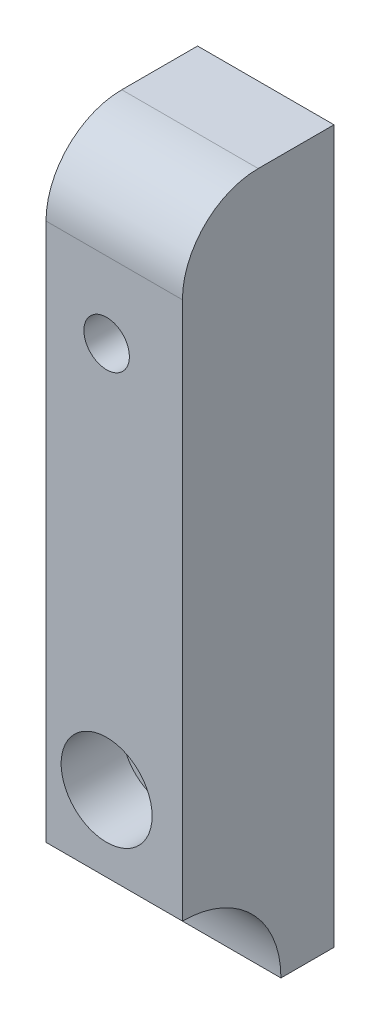
SolidWorks part; units mm, degrees
ref_plane "Front Plane" through (0, 0, 0) normal (0, 0, 1) x (1, 0, 0)
ref_plane "Top Plane" through (0, 0, 0) normal (0, 1, 0) x (1, 0, 0)
ref_plane "Right Plane" through (0, 0, 0) normal (1, 0, 0) x (0, 0, -1)
sketch "Sketch1" plane through (0, 0, 0) normal (0, 0, 1) x (1, 0, 0)
  line L1 (0, 0) -> (10, 0)
  line L2 (0, 0) -> (0, 47)
  line L3 (0, 47) -> (10, 47)
  line L4 (10, 0) -> (10, 47)
  dimension "D1" = 47
  dimension "D2" = 10
extrude "Boss-Extrude1" add sketch "Sketch1" along normal blind 10
sketch "Sketch2" plane through (0, 0, 10) normal (0, 0, 1) x (1, 0, 0)
  circle A0 centre (5, 37) radius 1.5
  circle A1 centre (5, 11.5) radius 1.5
  dimension "D3" = 3
  dimension "D4" = 3
  dimension "D1" = 10
  dimension "D2" = 11.5
extrude "Cut-Extrude1" cut sketch "Sketch2" against normal blind 10
fillet "Fillet1" radius 5 1 edges at (5, 47, 10)
sketch "Sketch3" plane through (0, 0, 0) normal (-1, 0, 0) x (0, 0, 1)
  line L1 (0, 47) -> (10, 47)
  line L2 (0, 47) -> (0, 0)
  line L3 (0, 0) -> (10, 0)
  line L4 (10, 47) -> (10, 0)
extrude "Cut-Extrude2" cut sketch "Sketch3" against normal blind 1
sketch "Sketch4" plane through (1, 0, 0) normal (-1, 0, 0) x (0, 0, 1)
  circle A0 centre (10, 0) radius 6.5
  dimension "D1" = 13
extrude "Cut-Extrude3" cut sketch "Sketch4" against normal blind 22
sketch "Sketch5" plane through (0, 0, 10) normal (0, 0, 1) x (1, 0, 0)
  circle A0 centre (5, 11.5) radius 3
  dimension "D1" = 6
extrude "Cut-Extrude4" cut sketch "Sketch5" against normal blind 4
